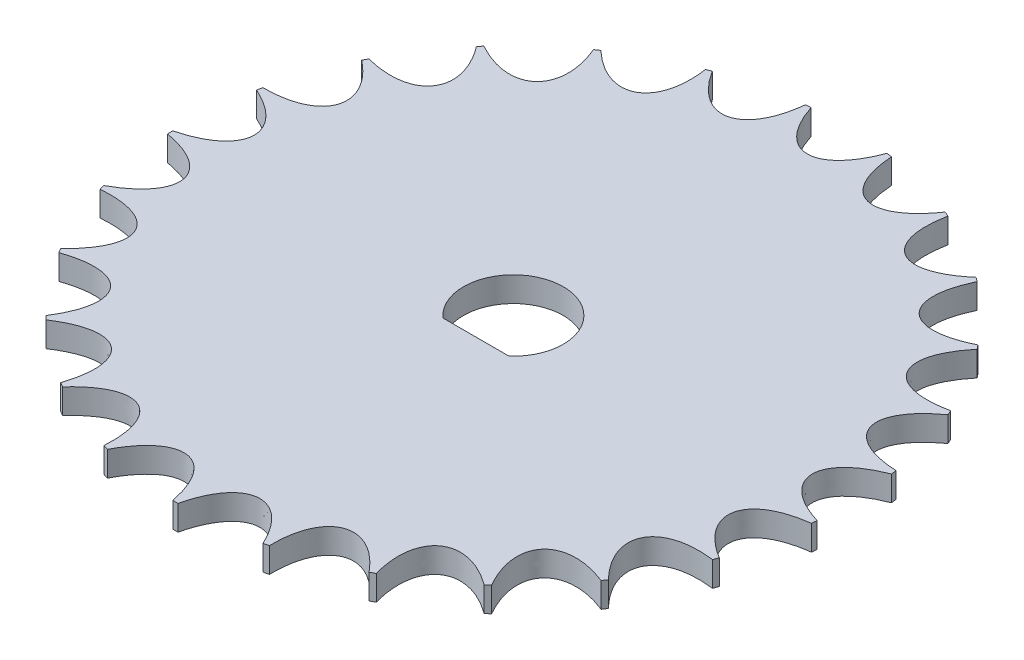
SolidWorks part; units mm, degrees
ref_plane "Front Plane" through (0, 0, 0) normal (0, 0, 1) x (1, 0, 0)
ref_plane "Top Plane" through (0, 0, 0) normal (0, 1, 0) x (1, 0, 0)
ref_plane "Right Plane" through (0, 0, 0) normal (1, 0, 0) x (0, 0, -1)
sketch "Sketch1" plane through (0, 0, 0) normal (0, 1, 0) x (1, 0, 0)
  line L0 (0, 0) -> (14.0773, 22.4517) construction
  line L1 (0, 0) -> (19.2186, 18.2454) construction
  line L2 (0, 0) -> (17.7301, 21.6713) construction
  circle A0 centre (0, 0) radius 26.5
  circle A1 centre (0, 0) radius 28 construction
  circle A2 centre (0, 0) radius 23 construction
  dimension "D1" = 53
  dimension "D2" = 46
  dimension "D3" = 14.4
  dimension "D4" = 7.2
extrude "Boss-Extrude1" add sketch "Sketch1" along normal blind 2
sketch "Sketch2" plane through (0, 2, 0) normal (0, 1, 0) x (1, 0, 0)
  line L0 (0, 0) -> (16.0666, 21.074) construction
  line L1 (0, 0) -> (19.633, 19.9636) construction
  line L2 (0, 0) -> (20.8028, 16.4163) construction
  circle A0 centre (0, 0) radius 28 construction
  circle A1 centre (0, 0) radius 23 construction
  arc A2 (20.6706, 16.5824) -> (16.235, 20.9446) centre (0, 0) ccw
  conic Q0 (16.235, 20.9446) -> (20.6706, 16.5824) control (12.1352, 12.3396) rho 0.367334
  dimension "D1" = 14.4
  dimension "D2" = 7.2
extrude "Cut-Extrude1" cut sketch "Sketch2" against normal blind 2
pattern_circular "CirPattern2" count 25 over 360 about axis through (0, 2, 0) along (0, -1, 0) of "Cut-Extrude1"
sketch "Sketch4" plane through (0, 2, 0) normal (0, 1, 0) x (1, 0, 0)
  line L1 (0, 0) -> (0, -3) construction
  line L2 (2.6458, -3) -> (-2.6458, -3)
  arc A0 (2.6458, -3) -> (-2.6458, -3) centre (0, 0) ccw
  point P8 (0, -3)
  dimension "D1" = 8
  dimension "D2" = 3
extrude "Cut-Extrude2" cut sketch "Sketch4" against normal blind 2
